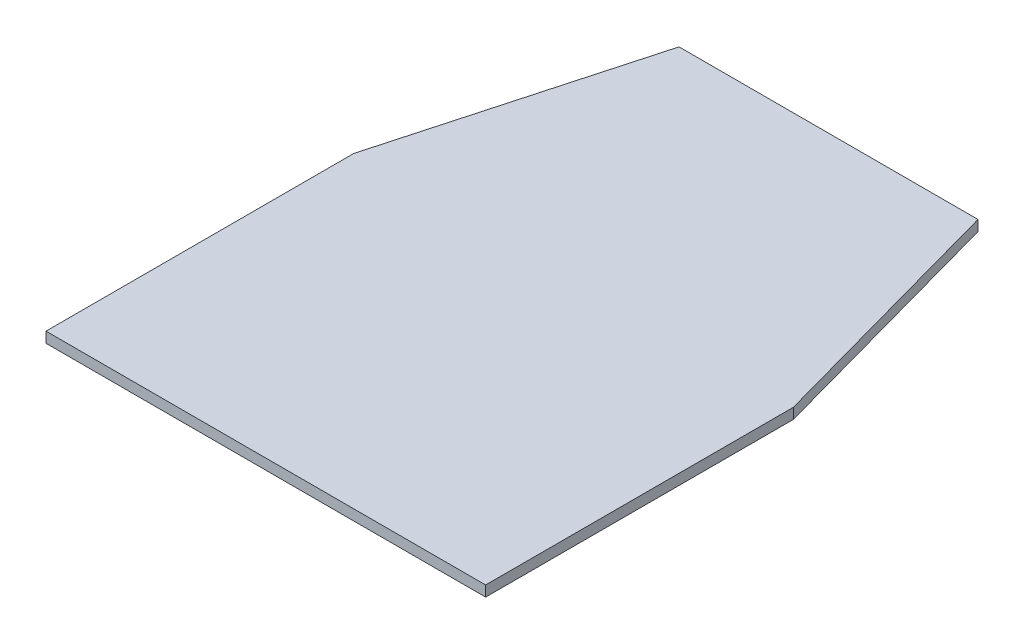
SolidWorks part; units mm, degrees
ref_plane "Front Plane" through (0, 0, 0) normal (0, 0, 1) x (1, 0, 0)
ref_plane "Top Plane" through (0, 0, 0) normal (0, 1, 0) x (1, 0, 0)
ref_plane "Right Plane" through (0, 0, 0) normal (1, 0, 0) x (0, 0, -1)
sketch "Sketch1" plane through (0, 0, 0) normal (0, 1, 0) x (1, 0, 0)
  line L1 (0, 0) -> (250, 0)
  line L2 (0, 0) -> (0, 175)
  line L3 (40, 320) -> (210, 320)
  line L4 (250, 0) -> (250, 175)
  line L6 (250, 0) -> (250, 175)
  line L7 (250, 175) -> (210, 320)
  line L8 (0, 175) -> (40, 320)
  dimension "D1" = 250
  dimension "D2" = 320
  dimension "D3" = 175
  dimension "D4" = 170
  dimension "D5" = 175
extrude "Boss-Extrude1" add sketch "Sketch1" along normal blind 6 contours L1 L2 L8 L3 L7 L6
